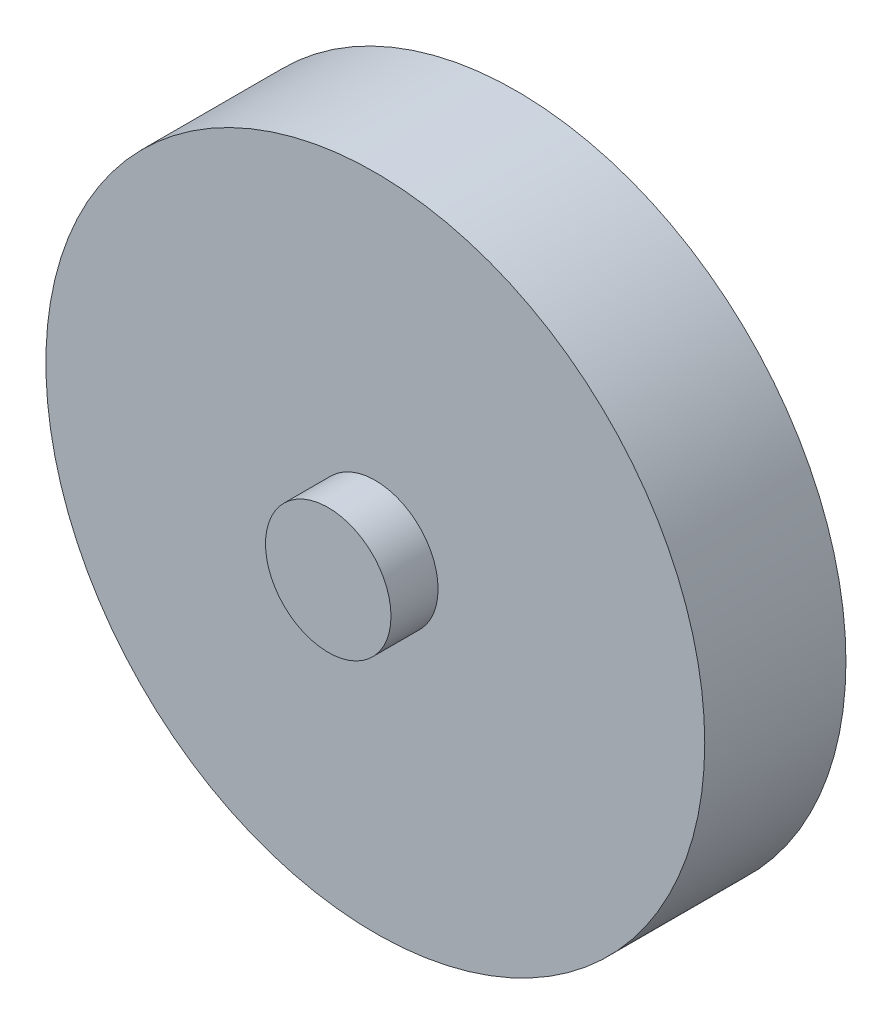
SolidWorks part; units mm, degrees
ref_plane "前视基准面" through (0, 0, 0) normal (0, 0, 1) x (1, 0, 0)
ref_plane "上视基准面" through (0, 0, 0) normal (0, 1, 0) x (1, 0, 0)
ref_plane "右视基准面" through (0, 0, 0) normal (1, 0, 0) x (0, 0, -1)
other "Configuration Table"
sketch "草图1" plane through (0, 0, 0) normal (0, 0, 1) x (1, 0, 0)
  circle A0 centre (0, 0) radius 8
extrude "凸台-拉伸1" add sketch "草图1" along normal blind 24
sketch "草图2" plane through (0, 0, 0) normal (0, 0, 1) x (1, 0, 0)
  circle A0 centre (0, 0) radius 42
extrude "凸台-拉伸2" add sketch "草图2" along normal blind 18
sketch "草图3" plane through (0, 0, 0) normal (0, 0, -1) x (-1, 0, 0)
  circle A0 centre (0, 0) radius 42
sketch "草图4" plane through (0, 0, 0) normal (0, 0, 1) x (1, 0, 0)
  circle A0 centre (0, 0) radius 8
extrude "凸台-拉伸3" add sketch "草图4" along normal blind 6
sketch "草图5" plane through (0, 0, 24) normal (0, 0, 1) x (1, 0, 0)
  line L0 (-4.4239, 2.5376) -> (4.894, 1.4347)
  arc A0 (4.894, 1.4347) -> (-4.4239, 2.5376) centre (0, 0) cw
sketch "草图6" plane through (0, 0, 24) normal (0, 0, 1) x (1, 0, 0)
  line L0 (37.445, 2.0305) -> (37.5326, 2.0353)
  arc A0 (41.9931, 0.7606) -> (41.5951, 5.8179) centre (0, 0) ccw
  arc A1 (37.5326, 3.8521) -> (37.6744, 2.043) centre (0, 0) cw
sketch "草图7" plane through (0, 0, 24) normal (0, 0, 1) x (1, 0, 0)
  line L0 (36.6663, 7.8632) -> (36.7521, 7.8816)
  arc A0 (41.3571, 7.8816) -> (40.2699, 12.2828) centre (0, 0) ccw
  arc A1 (36.7521, 9.64) -> (37.1506, 7.9671) centre (0, 0) cw
sketch "草图8" plane through (0, 0, 24) normal (0, 0, 1) x (1, 0, 0)
  line L0 (34.9848, 13.5023) -> (35.0666, 13.5339)
  line L1 (35.0666, 15.226) -> (34.9848, 15.1904)
  arc A0 (39.7028, 13.5339) -> (37.713, 18.3632) centre (0, 0) ccw
  arc A1 (34.9848, 15.1904) -> (35.5822, 13.7329) centre (0, 0) cw
sketch "草图9" plane through (0, 0, 24) normal (0, 0, 1) x (1, 0, 0)
  line L0 (32.4419, 18.8089) -> (32.5178, 18.8529)
  line L1 (31.5608, 19.7422) -> (31.4872, 19.7422)
  arc A0 (37.0708, 19.7422) -> (34.4202, 24.0676) centre (0, 0) ccw
  arc A1 (31.4872, 19.7422) -> (32.1516, 18.6406) centre (0, 0) ccw
sketch "草图10" plane through (0, 0, 24) normal (0, 0, 1) x (1, 0, 0)
  line L0 (31.7105, 19.3814) -> (28.8397, 23.4407)
  arc A0 (31.4872, 19.7422) -> (32.1516, 18.6406) centre (0, 0) ccw construction
  arc A1 (33.5261, 25.2983) -> (30.2315, 29.1558) centre (0, 0) ccw
  arc A2 (27.9134, 25.2983) -> (29.2334, 23.7607) centre (0, 0) cw
sketch "草图11" plane through (0, 0, 24) normal (0, 0, 1) x (1, 0, 0)
  arc A0 (29.1558, 30.2315) -> (25.2983, 33.5261) centre (0, 0) ccw
  arc A1 (23.6524, 29.1001) -> (25.0418, 27.9134) centre (0, 0) cw
sketch "草图12" plane through (0, 0, 24) normal (0, 0, 1) x (1, 0, 0)
  arc A0 (24.0676, 34.4202) -> (19.7422, 37.0708) centre (0, 0) ccw
  arc A1 (18.8089, 32.4419) -> (20.3669, 31.4872) centre (0, 0) cw
sketch "草图13" plane through (0, 0, 24) normal (0, 0, 1) x (1, 0, 0)
  arc A0 (18.3868, 37.7615) -> (13.7, 39.7028) centre (0, 0) ccw
  arc A1 (13.7, 34.9848) -> (15.2195, 34.3511) centre (0, 0) cw
sketch "草图14" plane through (0, 0, 24) normal (0, 0, 1) x (1, 0, 0)
  arc A0 (12.2532, 40.1729) -> (7.3204, 41.3571) centre (0, 0) ccw
  arc A1 (7.3204, 36.6663) -> (9.6117, 36.1334) centre (0, 0) cw
sketch "草图15" plane through (0, 0, 24) normal (0, 0, 1) x (1, 0, 0)
  arc A0 (5.8179, 41.5951) -> (0.7606, 41.9931) centre (0, 0) ccw
  arc A1 (2.0305, 37.445) -> (3.8521, 37.3016) centre (0, 0) cw
sketch "草图16" plane through (0, 0, 24) normal (0, 0, 1) x (1, 0, 0)
  arc A0 (-0.7606, 41.9931) -> (-5.8179, 41.5951) centre (0, 0) ccw
  arc A1 (-3.8521, 37.3016) -> (-2.0305, 37.445) centre (0, 0) cw
sketch "草图17" plane through (0, 0, 24) normal (0, 0, 1) x (1, 0, 0)
  arc A0 (-7.3204, 41.3571) -> (-12.2532, 40.1729) centre (0, 0) ccw
  arc A1 (-9.64, 36.2398) -> (-7.8632, 36.6663) centre (0, 0) cw
sketch "草图18" plane through (0, 0, 24) normal (0, 0, 1) x (1, 0, 0)
  arc A0 (-13.7, 39.7028) -> (-18.3868, 37.7615) centre (0, 0) ccw
  arc A1 (-15.1904, 34.2856) -> (-13.5023, 34.9848) centre (0, 0) cw
sketch "草图19" plane through (0, 0, 24) normal (0, 0, 1) x (1, 0, 0)
  arc A0 (-19.7422, 37.0708) -> (-24.0676, 34.4202) centre (0, 0) ccw
  arc A1 (-19.7422, 31.4872) -> (-18.6406, 32.1516) centre (0, 0) ccw
sketch "草图20" plane through (0, 0, 24) normal (0, 0, 1) x (1, 0, 0)
  arc A0 (-25.2983, 33.5261) -> (-29.1558, 30.2315) centre (0, 0) ccw
  arc A1 (-25.2983, 27.9134) -> (-23.7607, 29.2334) centre (0, 0) cw
sketch "草图21" plane through (0, 0, 24) normal (0, 0, 1) x (1, 0, 0)
  arc A0 (-30.2315, 29.1558) -> (-33.5261, 25.2983) centre (0, 0) ccw
  arc A1 (-29.1001, 23.6524) -> (-27.9134, 25.0418) centre (0, 0) cw
sketch "草图22" plane through (0, 0, 24) normal (0, 0, 1) x (1, 0, 0)
  arc A0 (-34.4202, 24.0676) -> (-37.0708, 19.7422) centre (0, 0) ccw
  arc A1 (-32.4419, 18.8089) -> (-31.4872, 20.3669) centre (0, 0) cw
sketch "草图23" plane through (0, 0, 24) normal (0, 0, 1) x (1, 0, 0)
  arc A0 (-37.7615, 18.3868) -> (-39.7028, 13.7) centre (0, 0) ccw
  arc A1 (-34.9848, 13.7) -> (-34.3511, 15.2195) centre (0, 0) cw
sketch "草图24" plane through (0, 0, 24) normal (0, 0, 1) x (1, 0, 0)
  arc A0 (-40.1729, 12.2532) -> (-41.3571, 7.3204) centre (0, 0) ccw
  arc A1 (-36.6663, 7.3204) -> (-36.1334, 9.6117) centre (0, 0) cw
sketch "草图25" plane through (0, 0, 24) normal (0, 0, 1) x (1, 0, 0)
  arc A0 (-41.5951, 5.8179) -> (-41.9931, 0.7606) centre (0, 0) ccw
  arc A1 (-37.445, 2.0305) -> (-37.3016, 3.8521) centre (0, 0) cw
sketch "草图26" plane through (0, 0, 24) normal (0, 0, 1) x (1, 0, 0)
  arc A0 (-41.9931, -0.7606) -> (-41.5951, -5.8179) centre (0, 0) ccw
  arc A1 (-37.3016, -3.8521) -> (-37.445, -2.0305) centre (0, 0) cw
sketch "草图27" plane through (0, 0, 24) normal (0, 0, 1) x (1, 0, 0)
  arc A0 (-41.3571, -7.3204) -> (-40.1729, -12.2532) centre (0, 0) ccw
  arc A1 (-36.2398, -9.64) -> (-36.6663, -7.8632) centre (0, 0) cw
sketch "草图28" plane through (0, 0, 24) normal (0, 0, 1) x (1, 0, 0)
  arc A0 (-39.7028, -13.7) -> (-37.7615, -18.3868) centre (0, 0) ccw
  arc A1 (-34.2856, -15.1904) -> (-34.9848, -13.5023) centre (0, 0) cw
sketch "草图29" plane through (0, 0, 24) normal (0, 0, 1) x (1, 0, 0)
  arc A0 (-37.0708, -19.7422) -> (-34.4202, -24.0676) centre (0, 0) ccw
  arc A1 (-31.4872, -19.7422) -> (-32.1516, -18.6406) centre (0, 0) ccw
sketch "草图30" plane through (0, 0, 24) normal (0, 0, 1) x (1, 0, 0)
  arc A0 (-33.5261, -25.2983) -> (-30.2315, -29.1558) centre (0, 0) ccw
  arc A1 (-27.9134, -25.2983) -> (-29.2334, -23.7607) centre (0, 0) cw
sketch "草图31" plane through (0, 0, 24) normal (0, 0, 1) x (1, 0, 0)
  arc A0 (-29.1558, -30.2315) -> (-25.2983, -33.5261) centre (0, 0) ccw
  arc A1 (-23.6524, -29.1001) -> (-25.0418, -27.9134) centre (0, 0) cw
sketch "草图32" plane through (0, 0, 24) normal (0, 0, 1) x (1, 0, 0)
  arc A0 (-24.0676, -34.4202) -> (-19.7422, -37.0708) centre (0, 0) ccw
  arc A1 (-18.8089, -32.4419) -> (-20.3669, -31.4872) centre (0, 0) cw
sketch "草图33" plane through (0, 0, 24) normal (0, 0, 1) x (1, 0, 0)
  arc A0 (-18.3868, -37.7615) -> (-13.7, -39.7028) centre (0, 0) ccw
  arc A1 (-13.7, -34.9848) -> (-15.2195, -34.3511) centre (0, 0) cw
sketch "草图34" plane through (0, 0, 24) normal (0, 0, 1) x (1, 0, 0)
  arc A0 (-12.2532, -40.1729) -> (-7.3204, -41.3571) centre (0, 0) ccw
  arc A1 (-7.3204, -36.6663) -> (-9.6117, -36.1334) centre (0, 0) cw
sketch "草图35" plane through (0, 0, 24) normal (0, 0, 1) x (1, 0, 0)
  arc A0 (-5.8179, -41.5951) -> (-0.7606, -41.9931) centre (0, 0) ccw
  arc A1 (-2.0305, -37.445) -> (-3.8521, -37.3016) centre (0, 0) cw
sketch "草图36" plane through (0, 0, 24) normal (0, 0, 1) x (1, 0, 0)
  arc A0 (0.7606, -41.9931) -> (5.8179, -41.5951) centre (0, 0) ccw
  arc A1 (3.8521, -37.3016) -> (2.0305, -37.445) centre (0, 0) cw
sketch "草图37" plane through (0, 0, 24) normal (0, 0, 1) x (1, 0, 0)
  arc A0 (7.3204, -41.3571) -> (12.2532, -40.1729) centre (0, 0) ccw
  arc A1 (9.64, -36.2398) -> (7.8632, -36.6663) centre (0, 0) cw
sketch "草图38" plane through (0, 0, 24) normal (0, 0, 1) x (1, 0, 0)
  arc A0 (13.7, -39.7028) -> (18.3868, -37.7615) centre (0, 0) ccw
  arc A1 (15.1904, -34.2856) -> (13.5023, -34.9848) centre (0, 0) cw
sketch "草图39" plane through (0, 0, 24) normal (0, 0, 1) x (1, 0, 0)
  arc A0 (19.7422, -37.0708) -> (24.0676, -34.4202) centre (0, 0) ccw
  arc A1 (19.7422, -31.4872) -> (18.6406, -32.1516) centre (0, 0) ccw
sketch "草图40" plane through (0, 0, 24) normal (0, 0, 1) x (1, 0, 0)
  arc A0 (25.2983, -33.5261) -> (29.1558, -30.2315) centre (0, 0) ccw
  arc A1 (25.2983, -27.9134) -> (23.7607, -29.2334) centre (0, 0) cw
sketch "草图41" plane through (0, 0, 24) normal (0, 0, 1) x (1, 0, 0)
  arc A0 (30.2315, -29.1558) -> (33.5261, -25.2983) centre (0, 0) ccw
  arc A1 (29.1001, -23.6524) -> (27.9134, -25.0418) centre (0, 0) cw
sketch "草图42" plane through (0, 0, 24) normal (0, 0, 1) x (1, 0, 0)
  arc A0 (34.4202, -24.0676) -> (37.0708, -19.7422) centre (0, 0) ccw
  arc A1 (32.4419, -18.8089) -> (31.4872, -20.3669) centre (0, 0) cw
sketch "草图43" plane through (0, 0, 24) normal (0, 0, 1) x (1, 0, 0)
  arc A0 (37.7615, -18.3868) -> (39.7028, -13.7) centre (0, 0) ccw
  arc A1 (34.9848, -13.7) -> (34.3511, -15.2195) centre (0, 0) cw
sketch "草图44" plane through (0, 0, 24) normal (0, 0, 1) x (1, 0, 0)
  arc A0 (40.1729, -12.2532) -> (41.3571, -7.3204) centre (0, 0) ccw
  arc A1 (36.6663, -7.3204) -> (36.1334, -9.6117) centre (0, 0) cw
sketch "草图45" plane through (0, 0, 24) normal (0, 0, 1) x (1, 0, 0)
  arc A0 (41.5951, -5.8179) -> (41.9931, -0.7606) centre (0, 0) ccw
  arc A1 (37.445, -2.0305) -> (37.3016, -3.8521) centre (0, 0) cw
